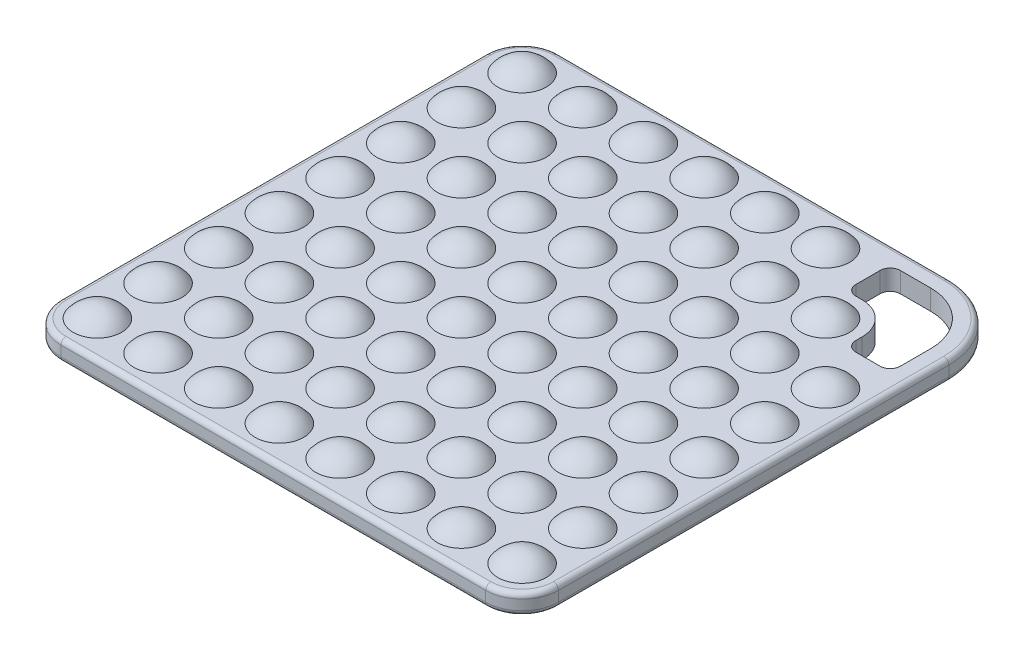
SolidWorks part; units mm, degrees
material "Rubber"
ref_plane "Front Plane" through (0, 0, 0) normal (0, 0, 1) x (1, 0, 0)
ref_plane "Top Plane" through (0, 0, 0) normal (0, 1, 0) x (1, 0, 0)
ref_plane "Right Plane" through (0, 0, 0) normal (1, 0, 0) x (0, 0, -1)
sketch "Sketch1" plane through (0, 0, 0) normal (0, 1, 0) x (1, 0, 0)
  line L1 (-105, 123) -> (88, 123)
  line L2 (-123, 105) -> (-123, -105)
  line L3 (-105, -123) -> (105, -123)
  line L4 (123, 88) -> (123, -105)
  line L5 (-123, 123) -> (123, -123) construction
  line L6 (-123, -123) -> (123, 123) construction
  arc A0 (105, -123) -> (123, -105) centre (105, -105) ccw
  arc A1 (-123, -105) -> (-105, -123) centre (-105, -105) ccw
  arc A2 (-105, 123) -> (-123, 105) centre (-105, 105) ccw
  arc A3 (88, 123) -> (123, 88) centre (88, 88) cw
  point P1 (0, 0)
  dimension "D2" = 18
  dimension "D3" = 35
  dimension "D1" = 246
  dimension "D4" = 246
extrude "Boss-Extrude1" add sketch "Sketch1" along normal blind 10
sketch "Sketch4" plane through (0, 10, 0) normal (0, 1, 0) x (1, 0, 0)
  line L0 (68, 109) -> (68, 97)
  line L1 (73, 92) -> (76, 92)
  line L2 (92, 76) -> (92, 73)
  line L3 (97, 68) -> (109, 68)
  line L4 (114, 73) -> (114, 88)
  line L5 (88, 114) -> (73, 114)
  arc A0 (123, 88) -> (88, 123) centre (88, 88) ccw construction
  arc A1 (123, 88) -> (88, 123) centre (88, 88) ccw
  arc A2 (76, 92) -> (92, 76) centre (76, 76) cw
  arc A3 (114, 88) -> (88, 114) centre (88, 88) ccw
  arc A4 (68, 109) -> (73, 114) centre (73, 109) cw
  arc A5 (68, 97) -> (73, 92) centre (73, 97) ccw
  arc A6 (109, 68) -> (114, 73) centre (109, 73) ccw
  arc A7 (92, 73) -> (97, 68) centre (97, 73) ccw
  point P13 (97.1962, 85.5441)
  dimension "D1" = 16
  dimension "D5" = 5
  dimension "D7" = 26
  dimension "D2" = 20
  dimension "D3" = 20
  dimension "D4" = 22
  dimension "D6" = 22
extrude "Cut-Extrude1" cut sketch "Sketch4" against normal up to next contours L2 A7 L3 A6 L4 A3 L5 A4 L0 A5 L1 A2
fillet "Fillet1" radius 2.5 16 edges at (117.7279, 0, 117.7279) (0, 0, 123) (-117.7279, 0, 117.7279) (-123, 0, 0) (-117.7279, 0, -117.7279) (-8.5, 0, -123) (112.7487, 0, -112.7487) (117.7279, 10, 117.7279) (0, 10, 123) (-117.7279, 10, 117.7279) (-123, 10, 0) (-117.7279, 10, -117.7279) (-8.5, 10, -123) (112.7487, 10, -112.7487) (123, 0, 8.5) (123, 10, 8.5)
ref_plane "Plane1" through (0, 0, 105) normal (0, 0, 1) x (1, 0, 0)
sketch "Sketch5" plane through (0, 0, 105) normal (0, 0, 1) x (1, 0, 0)
  line L0 (105, 10) -> (105, 16)
  line L1 (117, 10) -> (105, 10)
  arc A0 (105, 16) -> (117, 10) centre (105, 1) cw
  dimension "D2" = 15
  dimension "D1" = 6
revolve "Revolve1" add sketch "Sketch5" angle 360 about L0
pattern_linear "LPattern1" count 8 spacing 30 along (-1, 0, 0) count 8 spacing 30 along (0, 0, -1) skipping (0, 6), (0, 7), (1, 7) of "Revolve1"
